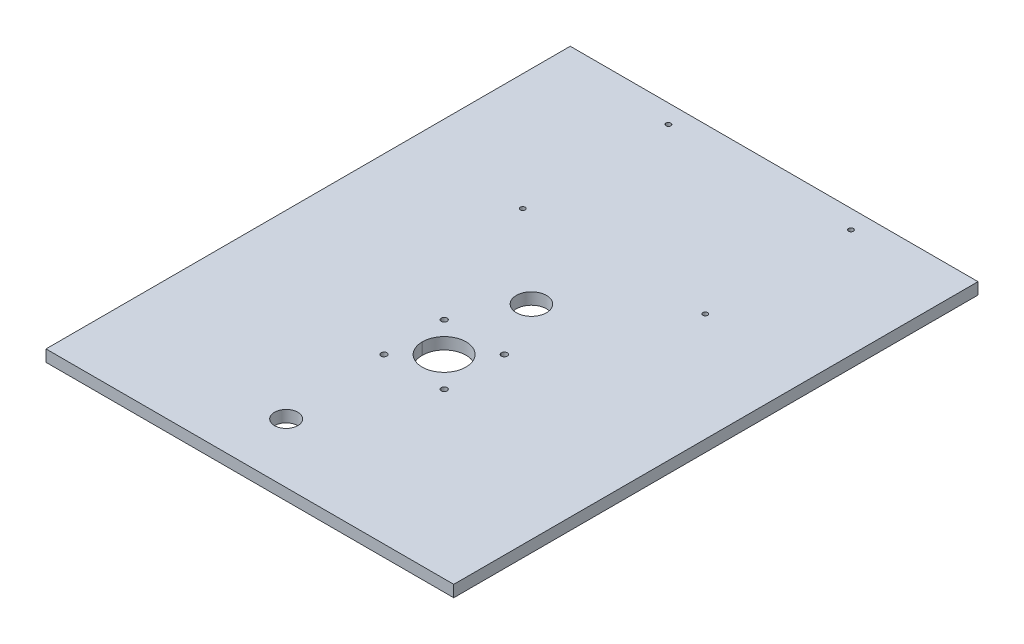
SolidWorks part; units mm, degrees
ref_plane "Front Plane" through (0, 0, 0) normal (0, 0, 1) x (1, 0, 0)
ref_plane "Top Plane" through (0, 0, 0) normal (0, 1, 0) x (1, 0, 0)
ref_plane "Right Plane" through (0, 0, 0) normal (1, 0, 0) x (0, 0, -1)
sketch "Sketch1" plane through (0, 0, 0) normal (0, 1, 0) x (1, 0, 0)
  line L4 (-105, -145) -> (105, -145)
  line L5 (105, -145) -> (105, 125)
  line L6 (105, 125) -> (-105, 125)
  line L7 (-105, 125) -> (-105, -145)
  circle A1 centre (0, 0) radius 7.75
extrude "Boss-Extrude2" add sketch "Sketch1" along normal blind 6
sketch "Sketch3" plane through (0, 0, 0) normal (0, -1, 0) x (1, 0, 0)
  line L0 (0, 0) -> (0, 45) construction
  line L1 (15.5, 29.5) -> (15.5, 29.4) construction
  line L2 (15.5, 29.5) -> (-15.5, 29.5) construction
  line L3 (15.5, 29.5) -> (15.5, 60.5) construction
  line L4 (15.5, 60.5) -> (-15.5, 60.5) construction
  line L5 (-15.5, 29.5) -> (-15.5, 60.5) construction
  line L6 (15.5, 29.5) -> (-15.5, 60.5) construction
  line L7 (15.5, 60.5) -> (-15.5, 29.5) construction
  line L8 (17, 29.5) -> (17, 29.4)
  line L9 (14, 29.5) -> (14, 29.4)
  line L10 (15.5, 60.5) -> (15.5, 60.4) construction
  line L11 (17, 60.5) -> (17, 60.4)
  line L12 (14, 60.5) -> (14, 60.4)
  line L13 (-15.5, 29.5) -> (-15.5, 29.4) construction
  line L14 (-17, 29.5) -> (-17, 29.4)
  line L15 (-14, 29.5) -> (-14, 29.4)
  line L16 (-15.5, 60.5) -> (-15.5, 60.4) construction
  line L17 (-17, 60.5) -> (-17, 60.4)
  line L18 (-14, 60.5) -> (-14, 60.4)
  line L19 (0, 45) -> (0, 44.9) construction
  line L20 (11.25, 45) -> (11.25, 44.9)
  line L21 (-11.25, 45) -> (-11.25, 44.9)
  circle A0 centre (0, 45) radius 11.25 construction
  arc A1 (17, 29.5) -> (14, 29.5) centre (15.5, 29.5) ccw
  arc A2 (14, 29.4) -> (17, 29.4) centre (15.5, 29.4) ccw
  arc A3 (17, 60.5) -> (14, 60.5) centre (15.5, 60.5) ccw
  arc A4 (14, 60.4) -> (17, 60.4) centre (15.5, 60.4) ccw
  arc A5 (-17, 29.5) -> (-14, 29.5) centre (-15.5, 29.5) cw
  arc A6 (-14, 29.4) -> (-17, 29.4) centre (-15.5, 29.4) cw
  arc A7 (-17, 60.5) -> (-14, 60.5) centre (-15.5, 60.5) cw
  arc A8 (-14, 60.4) -> (-17, 60.4) centre (-15.5, 60.4) cw
  arc A9 (11.25, 45) -> (-11.25, 45) centre (0, 45) ccw
  arc A10 (-11.25, 44.9) -> (11.25, 44.9) centre (0, 44.9) ccw
  point P9 (15.5, 29.45)
  point P15 (15.5, 60.45)
  point P23 (-15.5, 29.45)
  point P30 (-15.5, 60.45)
  point P36 (0, 44.95)
  dimension "D1" = 31
  dimension "D3" = 22.5
  dimension "D5" = 1.5
  dimension "D6" = 1.5
  dimension "D9" = 11.25
  dimension "D2" = 31
  dimension "D4" = 0.1
  dimension "D7" = 0.1
  dimension "D8" = 0.1
extrude "Cut-Extrude1" cut sketch "Sketch3" against normal blind 10
sketch "Sketch4" plane through (0, 0, 0) normal (0, -1, 0) x (1, 0, 0)
  circle A0 centre (49.1703, -115.3822) radius 1.25
  circle A1 centre (-44.8297, -115.3822) radius 1.25
  circle A2 centre (49.1703, -40.3822) radius 1.25
  circle A3 centre (-44.8297, -40.3822) radius 1.25
  dimension "D1" = 2.5
extrude "Cut-Extrude2" cut sketch "Sketch4" against normal blind 10
sketch "Sketch5" plane through (0, 6, 0) normal (0, 1, 0) x (1, 0, 0)
  circle A0 centre (-11.9275, -114.3873) radius 6
extrude "Cut-Extrude3" cut sketch "Sketch5" against normal blind 10
